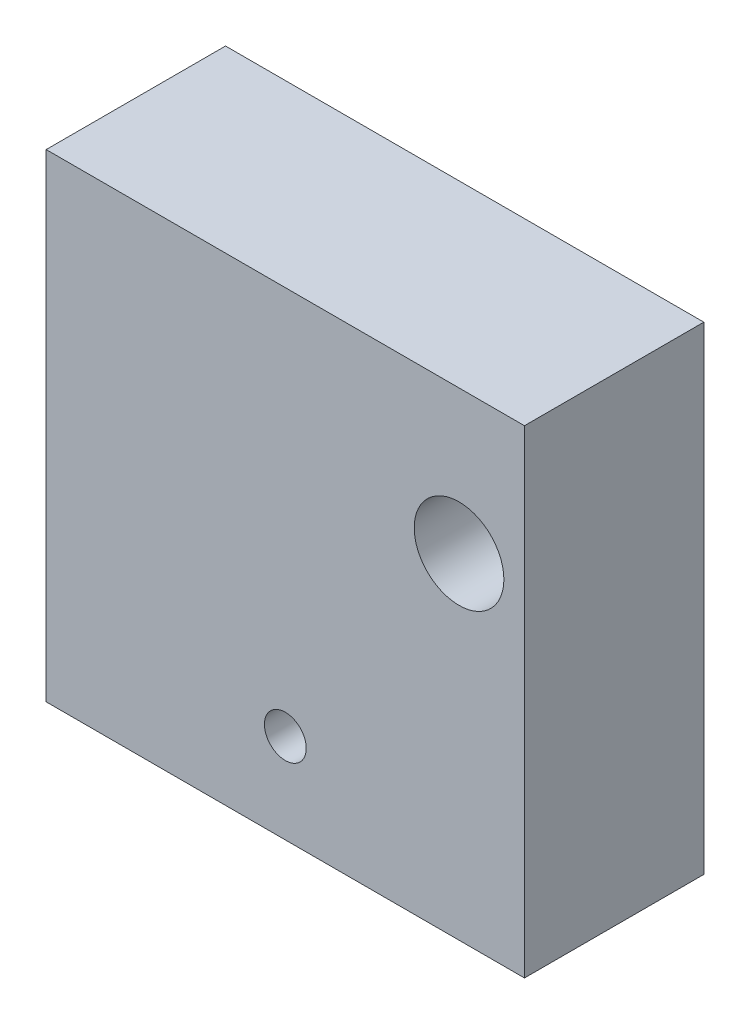
SolidWorks part; units mm, degrees
material "Balsa"
ref_plane "Plan de face" through (0, 0, 0) normal (0, 0, 1) x (1, 0, 0)
ref_plane "Plan de dessus" through (0, 0, 0) normal (0, 1, 0) x (1, 0, 0)
ref_plane "Plan de droite" through (0, 0, 0) normal (1, 0, 0) x (0, 0, -1)
sketch "Sketch1" plane through (0, 0, 0) normal (0, 0, 1) x (1, 0, 0)
  line L1 (-40, -40) -> (40, -40)
  line L2 (-40, -40) -> (-40, 40)
  line L3 (-40, 40) -> (40, 40)
  line L4 (40, -40) -> (40, 40)
  line L5 (-40, -40) -> (40, 40) construction
  line L6 (-40, 40) -> (40, -40) construction
  point P0 (0, 0)
  dimension "D1" = 80
  dimension "D2" = 80
extrude "Boss-Extrude1" add sketch "Sketch1" along normal blind 30
sketch "Sketch3" plane through (0, 0, 0) normal (0, 0, -1) x (-1, 0, 0)
  line L0 (40, -40) -> (-40, -40) construction
  line L1 (-20, -40) -> (20, -40)
  line L2 (-20, -40) -> (-20, -15)
  line L3 (-20, -15) -> (20, -15)
  line L4 (20, -40) -> (20, -15)
  line L5 (-40, -40) -> (-40, 40) construction
  line L6 (40, 40) -> (40, -40) construction
  dimension "D1" = 20
  dimension "D2" = 20
  dimension "D3" = 25
extrude "Cut-Extrude2" cut sketch "Sketch3" against normal blind 20
sketch "Sketch4" plane through (0, 0, 20) normal (0, 0, -1) x (-1, 0, 0)
  line L0 (-40, -40) -> (-40, 40) construction
  line L1 (40, -40) -> (-40, -40) construction
  circle A0 centre (0, -25) radius 3.5
  dimension "D1" = 7
  dimension "D2" = 40
  dimension "D3" = 15
extrude "Cut-Extrude3" cut sketch "Sketch4" against normal through all
sketch "Sketch6" plane through (0, 0, 30) normal (0, 0, 1) x (1, 0, 0)
  line L0 (-40, -40) -> (40, -40) construction
  circle A0 centre (29.0563, 16) radius 7.5
  dimension "D1" = 15
  dimension "D2" = 56
extrude "Cut-Extrude5" cut sketch "Sketch6" against normal through all
